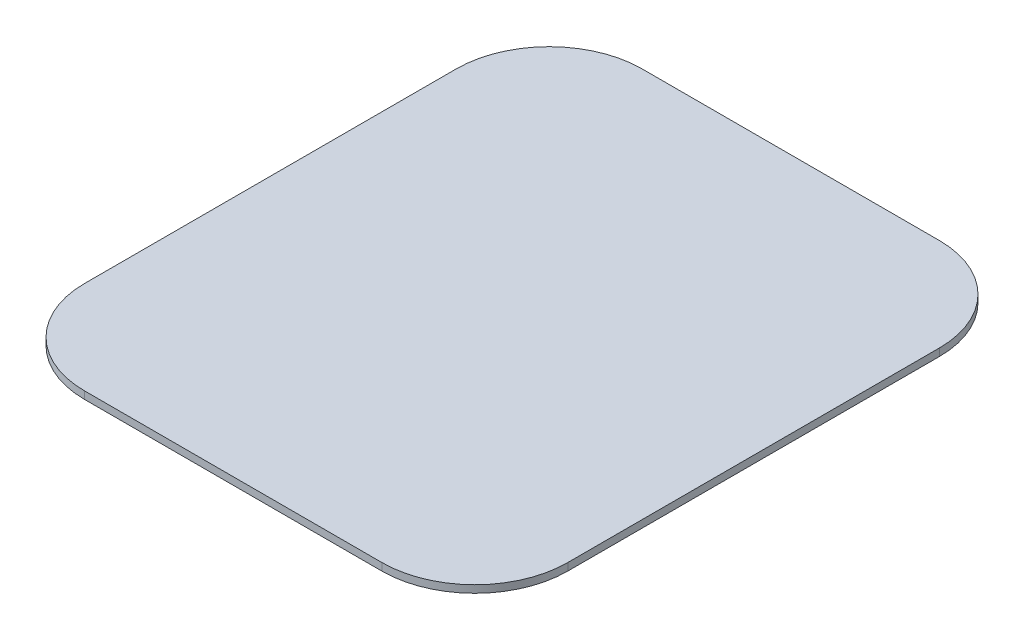
SolidWorks part; units mm, degrees
material "6063-O"
ref_plane "Plano frontal" through (0, 0, 0) normal (0, 0, 1) x (1, 0, 0)
ref_plane "Plano superior" through (0, 0, 0) normal (0, 1, 0) x (1, 0, 0)
ref_plane "Plano direito" through (0, 0, 0) normal (1, 0, 0) x (0, 0, -1)
sketch "Chapa inferior" plane through (0, 0, 0) normal (0, 1, 0) x (1, 0, 0)
  line L1 (-160, 300) -> (160, 300)
  line L2 (-260, 200) -> (-260, -200)
  line L3 (-160, -300) -> (160, -300)
  line L4 (260, 200) -> (260, -200)
  line L5 (-260, 300) -> (260, -300) construction
  line L6 (-260, -300) -> (260, 300) construction
  arc A0 (160, 300) -> (260, 200) centre (160, 200) cw
  arc A1 (160, -300) -> (260, -200) centre (160, -200) ccw
  arc A2 (-260, -200) -> (-160, -300) centre (-160, -200) ccw
  arc A3 (-160, 300) -> (-260, 200) centre (-160, 200) ccw
  point P0 (0, 0)
  dimension "D3" = 100
  dimension "D4" = 100
  dimension "D5" = 100
  dimension "D6" = 100
  dimension "D1" = 520
  dimension "D2" = 600
extrude "ChapaInferior" add sketch "Chapa inferior" along normal mid plane 8
